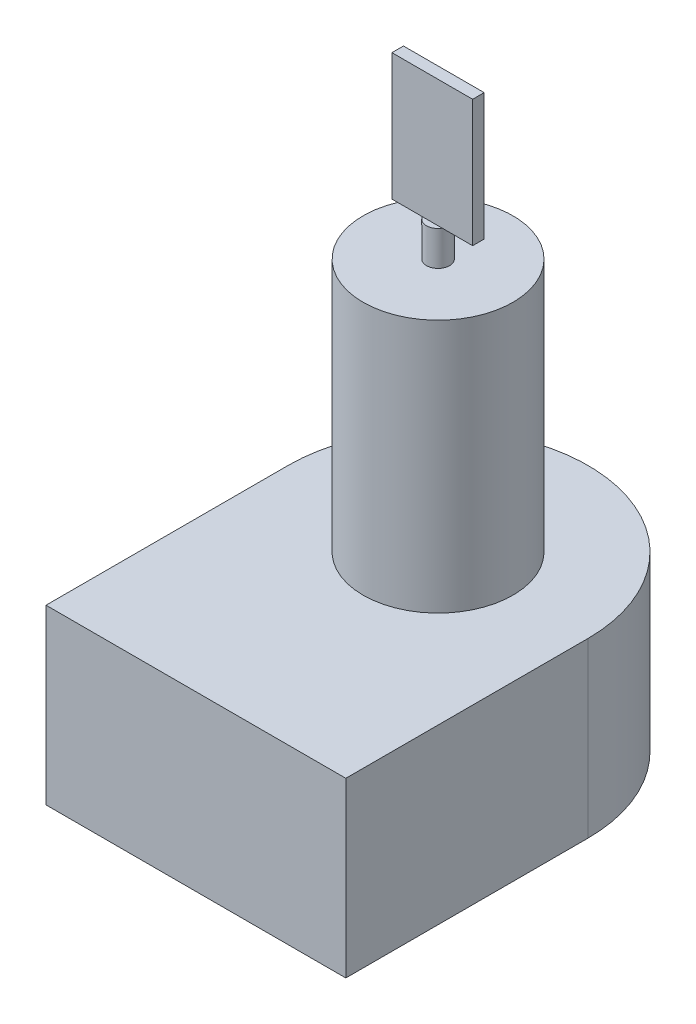
SolidWorks part; units mm, degrees
ref_plane "Front Plane" through (0, 0, 0) normal (0, 0, 1) x (1, 0, 0)
ref_plane "Top Plane" through (0, 0, 0) normal (0, 1, 0) x (1, 0, 0)
ref_plane "Right Plane" through (0, 0, 0) normal (1, 0, 0) x (0, 0, -1)
sketch "Sketch1" plane through (0, 0, 0) normal (0, 1, 0) x (1, 0, 0)
  line L0 (-13, 0) -> (-13, -21)
  line L1 (-13, -21) -> (13, -21)
  line L2 (13, -21) -> (13, 0)
  arc A0 (13, 0) -> (-13, 0) centre (0, 0) ccw
  point P6 (0, 13)
  dimension "D1" = 26
  dimension "D2" = 34
extrude "Boss-Extrude1" add sketch "Sketch1" along normal blind 15
sketch "Sketch2" plane through (0, 15, 0) normal (0, 1, 0) x (1, 0, 0)
  circle A0 centre (0, 0) radius 6.5
  dimension "D1" = 13
extrude "Boss-Extrude2" add sketch "Sketch2" along normal blind 22
sketch "Sketch3" plane through (0, 37, 0) normal (0, 1, 0) x (1, 0, 0)
  circle A0 centre (0, 0) radius 1
  dimension "D1" = 2
extrude "Boss-Extrude3" add sketch "Sketch3" along normal blind 3
sketch "Sketch4" plane through (0, 40, 0) normal (0, 1, 0) x (1, 0, 0)
  line L1 (-3.5, 0.5) -> (3.5, 0.5)
  line L2 (-3.5, 0.5) -> (-3.5, -0.5)
  line L3 (-3.5, -0.5) -> (3.5, -0.5)
  line L4 (3.5, 0.5) -> (3.5, -0.5)
  line L5 (-3.5, 0.5) -> (3.5, -0.5) construction
  line L6 (-3.5, -0.5) -> (3.5, 0.5) construction
  point P0 (0, 0)
  dimension "D1" = 1
  dimension "D2" = 7
extrude "Boss-Extrude4" add sketch "Sketch4" along normal blind 11
